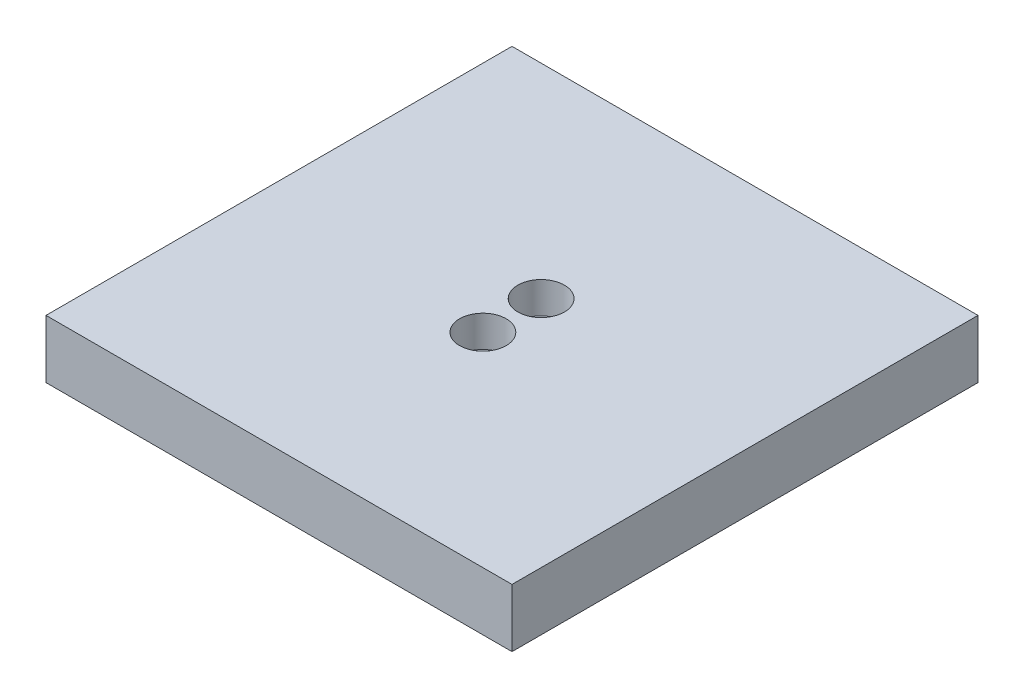
SolidWorks part; units mm, degrees
ref_plane "前视基准面" through (0, 0, 0) normal (0, 0, 1) x (1, 0, 0)
ref_plane "上视基准面" through (0, 0, 0) normal (0, 1, 0) x (1, 0, 0)
ref_plane "右视基准面" through (0, 0, 0) normal (1, 0, 0) x (0, 0, -1)
other "Configuration Table"
sketch "草图1" plane through (0, 0, 0) normal (0, 1, 0) x (1, 0, 0)
  line L1 (0, 0) -> (40, 0)
  line L2 (0, 0) -> (0, -40)
  line L3 (0, -40) -> (40, -40)
  line L4 (40, 0) -> (40, -40)
  dimension "D1" = 40
extrude "凸台-拉伸1" add sketch "草图1" along normal blind 5
sketch "草图2" plane through (0, 5, 0) normal (0, 1, 0) x (1, 0, 0)
  line L0 (0, -20) -> (40, -20) construction
  line L1 (0, 0) -> (0, -40) construction
  line L2 (40, -40) -> (40, 0) construction
  line L6 (20, -17.5) -> (20, -20) construction
  line L7 (20, -20) -> (20, -22.5) construction
  circle A0 centre (20, -17.5) radius 1.2
  circle A1 centre (20, -22.5) radius 1.2
  dimension "D2" = 2.4
  dimension "D1" = 5
extrude "切除-拉伸1" cut sketch "草图2" against normal through all
sketch "草图3" plane through (0, 5, 0) normal (0, 1, 0) x (1, 0, 0)
  circle A0 centre (20, -17.5) radius 2
  circle A1 centre (20, -22.5) radius 2
  dimension "D1" = 4
extrude "切除-拉伸2" cut sketch "草图3" against normal blind 2.7
